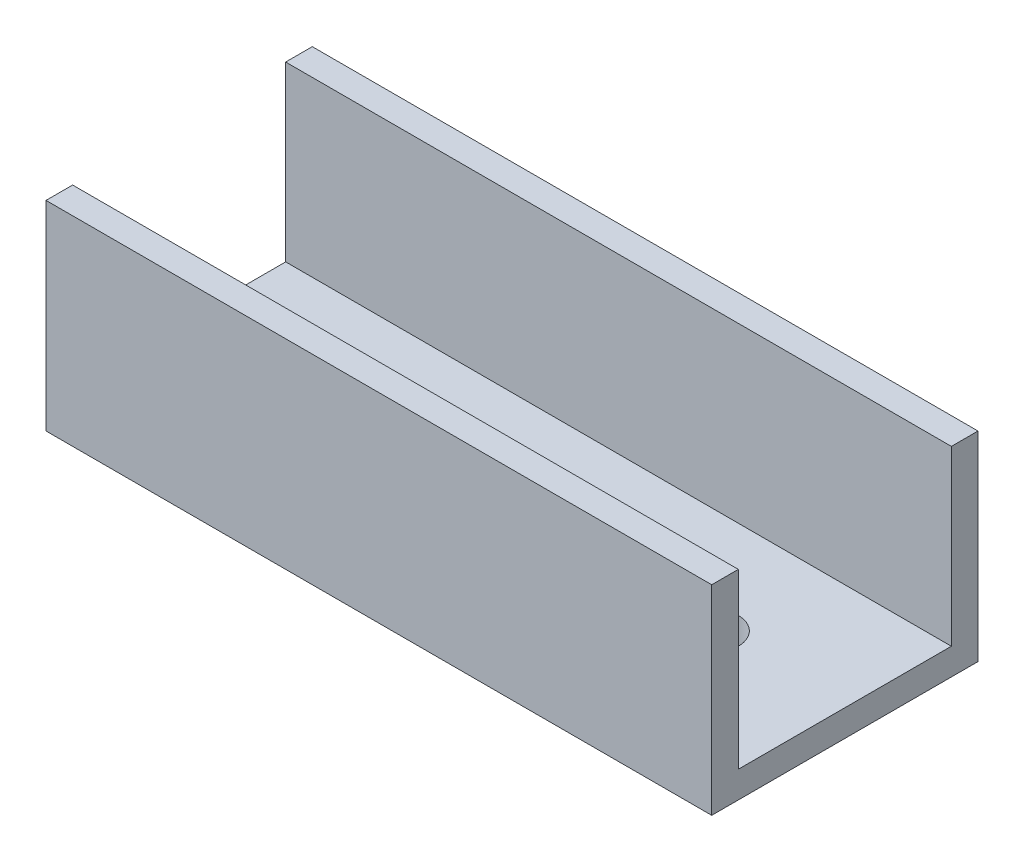
SolidWorks part; units mm, degrees
ref_plane "前视基准面" through (0, 0, 0) normal (0, 0, 1) x (1, 0, 0)
ref_plane "上视基准面" through (0, 0, 0) normal (0, 1, 0) x (1, 0, 0)
ref_plane "右视基准面" through (0, 0, 0) normal (1, 0, 0) x (0, 0, -1)
ref_plane "基准面1" through (-50, 0, 0) normal (1, 0, 0) x (0, 0, -1)
sketch "草图1" plane through (-50, 0, 0) normal (1, 0, 0) x (0, 0, -1)
  line L0 (20, 0) -> (-20, 0)
  line L1 (-20, 0) -> (-20, 30)
  line L2 (-20, 30) -> (-16, 30)
  line L3 (-16, 30) -> (-16, 4)
  line L4 (-16, 4) -> (16, 4)
  line L5 (16, 4) -> (16, 30)
  line L6 (16, 30) -> (20, 30)
  line L7 (20, 30) -> (20, 0)
extrude "凸台-拉伸1" add sketch "草图1" along normal blind 100
sketch "草图2" plane through (0, 0, 0) normal (0, 1, 0) x (1, 0, 0)
  circle A0 centre (-30, 0) radius 4
  circle A1 centre (0, 0) radius 4
  circle A2 centre (30, 0) radius 4
extrude "切除-拉伸1" cut sketch "草图2" along normal through all
